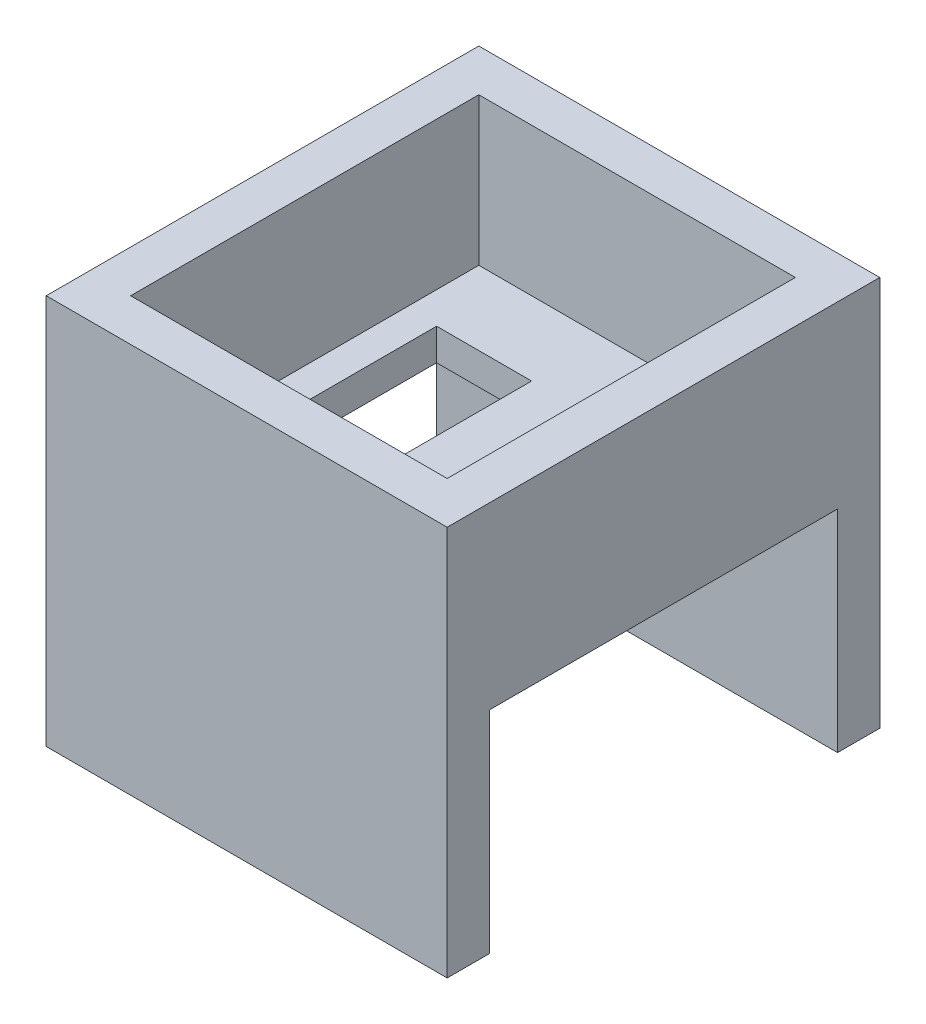
SolidWorks part; units mm, degrees
ref_plane "Front Plane" through (0, 0, 0) normal (0, 0, 1) x (1, 0, 0)
ref_plane "Top Plane" through (0, 0, 0) normal (0, 1, 0) x (1, 0, 0)
ref_plane "Right Plane" through (0, 0, 0) normal (1, 0, 0) x (0, 0, -1)
sketch "Sketch1" plane through (0, 0, 0) normal (0, 1, 0) x (1, 0, 0)
  line L1 (-19, 20.5) -> (19, 20.5)
  line L2 (-19, 20.5) -> (-19, -20.5)
  line L3 (-19, -20.5) -> (19, -20.5)
  line L4 (19, 20.5) -> (19, -20.5)
  line L5 (-19, 20.5) -> (19, -20.5) construction
  line L6 (-19, -20.5) -> (19, 20.5) construction
  point P0 (0, 0)
  dimension "D1" = 41
  dimension "D2" = 38
extrude "Boss-Extrude1" add sketch "Sketch1" along normal blind 37
sketch "Sketch2" plane through (0, 37, 0) normal (0, 1, 0) x (1, 0, 0)
  line L1 (-15, 16.5) -> (15, 16.5)
  line L2 (-15, 16.5) -> (-15, -16.5)
  line L3 (-15, -16.5) -> (15, -16.5)
  line L4 (15, 16.5) -> (15, -16.5)
  line L5 (-15, 16.5) -> (15, -16.5) construction
  line L6 (-15, -16.5) -> (15, 16.5) construction
  point P0 (0, 0)
  dimension "D1" = 33
  dimension "D2" = 30
extrude "Cut-Extrude1" cut sketch "Sketch2" against normal blind 14
sketch "Sketch3" plane through (-19, 0, 0) normal (-1, 0, 0) x (0, 0, 1)
  line L0 (-20.5, 0) -> (20.5, 0) construction
  line L1 (-16.5, 20) -> (16.5, 20)
  line L2 (-16.5, 20) -> (-16.5, 0)
  line L3 (-16.5, 0) -> (16.5, 0)
  line L4 (16.5, 20) -> (16.5, 0)
  line L5 (-16.5, 20) -> (16.5, 0) construction
  line L6 (-16.5, 0) -> (16.5, 20) construction
  point P0 (0, 10)
  dimension "D1" = 20
  dimension "D2" = 33
  dimension "D3" = 4
extrude "Cut-Extrude2" cut sketch "Sketch3" against normal through all
sketch "Sketch4" plane through (0, 23, 0) normal (0, 1, 0) x (1, 0, 0)
  line L1 (-12, 9.5) -> (-3, 9.5)
  line L2 (-12, 9.5) -> (-12, -9.5)
  line L3 (-12, -9.5) -> (-3, -9.5)
  line L4 (-3, 9.5) -> (-3, -9.5)
  line L5 (-12, 9.5) -> (-3, -9.5) construction
  line L6 (-12, -9.5) -> (-3, 9.5) construction
  point P0 (-7.5, 0)
  point P5 (-13.5423, 11.3669)
  dimension "D1" = 7
  dimension "D2" = 7
  dimension "D3" = 3
  dimension "D4" = 9
extrude "Cut-Extrude3" cut sketch "Sketch4" against normal through all
